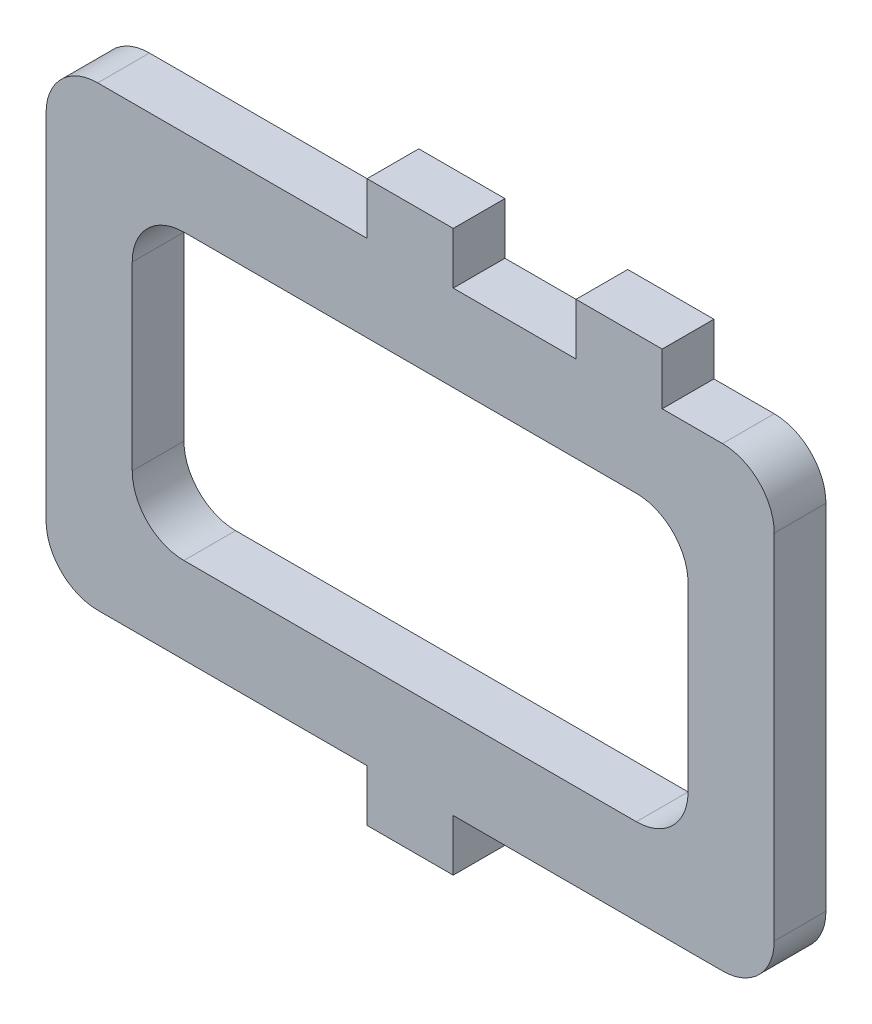
SolidWorks part; units mm, degrees
ref_plane "Alzado" through (0, 0, 0) normal (0, 0, 1) x (1, 0, 0)
ref_plane "Planta" through (0, 0, 0) normal (0, 1, 0) x (1, 0, 0)
ref_plane "Vista lateral" through (0, 0, 0) normal (1, 0, 0) x (0, 0, -1)
sketch "Croquis1" plane through (0, 0, 0) normal (0, 0, 1) x (1, 0, 0)
  line L0 (-102.6151, -90.722) -> (-86.9901, -90.722)
  line L1 (-90.4901, -61.222) -> (-90.4901, -64.222)
  line L2 (-107.6151, -61.222) -> (-105.1151, -61.222)
  line L3 (-90.4901, -64.222) -> (-86.9901, -64.222)
  line L4 (-107.6151, -90.722) -> (-123.2401, -90.722)
  line L5 (-105.1151, -61.222) -> (-102.6151, -61.222)
  line L6 (-102.6151, -61.222) -> (-102.6151, -64.222)
  line L7 (-95.4901, -61.222) -> (-95.4901, -64.222)
  line L8 (-95.4901, -64.222) -> (-102.6151, -64.222)
  line L9 (-123.2401, -64.222) -> (-107.6151, -64.222)
  line L10 (-107.6151, -90.722) -> (-107.6151, -93.722)
  line L11 (-107.6151, -93.722) -> (-102.6151, -93.722)
  line L12 (-102.6151, -93.722) -> (-102.6151, -90.722)
  line L15 (-83.9901, -87.722) -> (-83.9901, -67.222)
  line L24 (-107.6151, -61.222) -> (-107.6151, -64.222)
  line L31 (-95.4901, -61.222) -> (-90.4901, -61.222)
  line L32 (-126.2401, -87.722) -> (-126.2401, -67.222)
  arc A0 (-126.2401, -87.722) -> (-123.2401, -90.722) centre (-123.2401, -87.722) ccw
  arc A1 (-86.9901, -90.722) -> (-83.9901, -87.722) centre (-86.9901, -87.722) ccw
  arc A2 (-83.9901, -67.222) -> (-86.9901, -64.222) centre (-86.9901, -67.222) ccw
  arc A3 (-126.2401, -67.222) -> (-123.2401, -64.222) centre (-123.2401, -67.222) cw
  dimension "D1" = 3
extrude "Saliente-Extruir1" add sketch "Croquis1" along normal blind 3
sketch "Croquis2" plane through (0, 0, 3) normal (0, 0, 1) x (1, 0, 0)
  line L8 (-115.4276, -69.222) -> (-91.9901, -69.222)
  line L9 (-88.9901, -72.222) -> (-88.9901, -82.722)
  line L10 (-91.9901, -85.722) -> (-118.2401, -85.722)
  line L11 (-121.2401, -82.722) -> (-121.2401, -72.222)
  line L12 (-118.2401, -69.222) -> (-115.4276, -69.222)
  arc A0 (-118.2401, -85.722) -> (-121.2401, -82.722) centre (-118.2401, -82.722) cw
  arc A1 (-88.9901, -82.722) -> (-91.9901, -85.722) centre (-91.9901, -82.722) cw
  arc A2 (-91.9901, -69.222) -> (-88.9901, -72.222) centre (-91.9901, -72.222) cw
  arc A3 (-121.2401, -72.222) -> (-118.2401, -69.222) centre (-118.2401, -72.222) cw
  dimension "D1" = 3
extrude "Cortar-Extruir1" cut sketch "Croquis2" against normal blind 4
